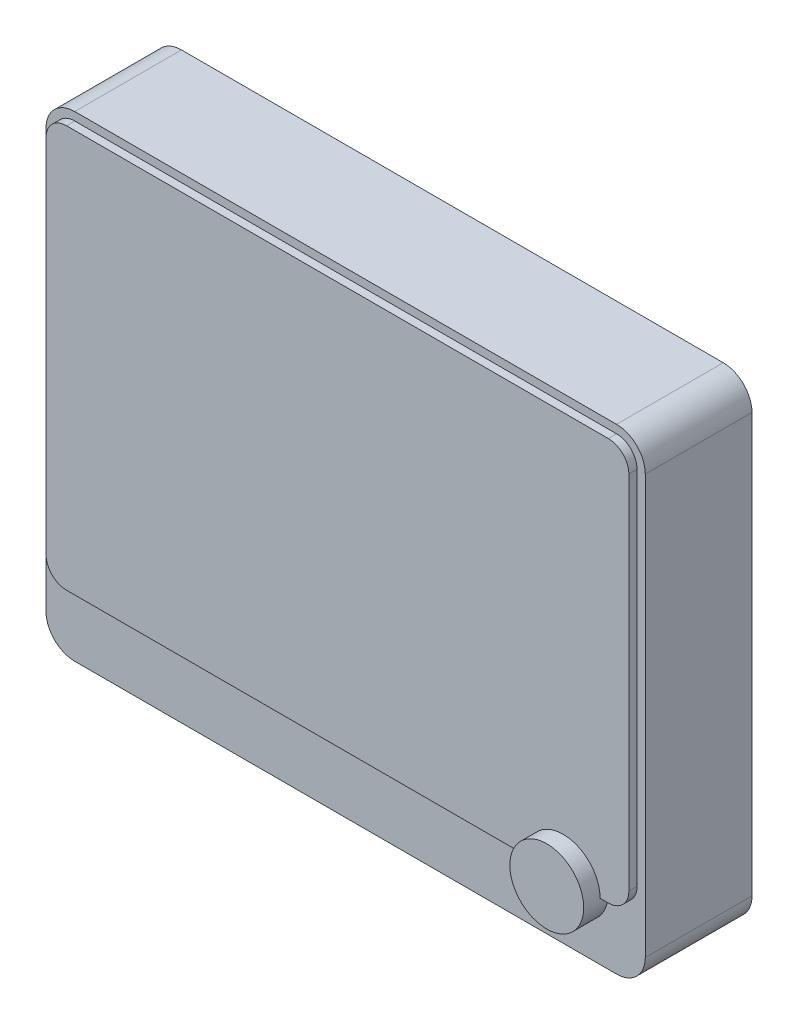
SolidWorks part; units mm, degrees
ref_plane "Front Plane" through (0, 0, 0) normal (0, 0, 1) x (1, 0, 0)
ref_plane "Top Plane" through (0, 0, 0) normal (0, 1, 0) x (1, 0, 0)
ref_plane "Right Plane" through (0, 0, 0) normal (1, 0, 0) x (0, 0, -1)
sketch "Sketch1" plane through (0, 0, 0) normal (0, 0, 1) x (1, 0, 0)
  line L0 (0, 0) -> (73, 0)
  line L1 (73, 0) -> (73, 58)
  line L2 (73, 58) -> (0, 58)
  line L3 (0, 58) -> (0, 0)
extrude "Boss-Extrude1" add sketch "Sketch1" along normal blind 13
fillet "Fillet1" radius 3.5 4 edges at (73, 0, 6.5) (0, 0, 6.5) (0, 58, 6.5) (73, 58, 6.5)
sketch "Sketch2" plane through (0, 0, 13) normal (0, 0, 1) x (1, 0, 0)
  line L5 (3.5, 8) -> (69.5, 8)
  line L8 (3.5, 1) -> (69.5, 1)
  line L9 (72, 3.5) -> (72, 54.5)
  line L10 (69.5, 57) -> (3.5, 57)
  line L11 (1, 54.5) -> (1, 3.5)
  line L13 (72, 10.5) -> (72, 54.5)
  line L14 (69.5, 57) -> (3.5, 57)
  line L15 (1, 54.5) -> (1, 10.5)
  arc A4 (1, 10.5) -> (3.5, 8) centre (3.5, 10.5) ccw
  arc A5 (72, 10.5) -> (69.5, 8) centre (69.5, 10.5) cw
  arc A8 (69.5, 1) -> (72, 3.5) centre (69.5, 3.5) ccw
  arc A9 (72, 54.5) -> (69.5, 57) centre (69.5, 54.5) ccw
  arc A10 (3.5, 57) -> (1, 54.5) centre (3.5, 54.5) ccw
  arc A11 (1, 3.5) -> (3.5, 1) centre (3.5, 3.5) ccw
  arc A13 (72, 54.5) -> (69.5, 57) centre (69.5, 54.5) ccw
  arc A14 (3.5, 57) -> (1, 54.5) centre (3.5, 54.5) ccw
  dimension "D1" = 1
extrude "Boss-Extrude2" add sketch "Sketch2" along normal blind 1
sketch "Sketch3" plane through (0, 0, 13) normal (0, 0, 1) x (1, 0, 0)
  line L2 (3.5, 8) -> (69.5, 8) construction
  circle A0 centre (64, 8) radius 4.5
extrude "Boss-Extrude3" add sketch "Sketch3" along normal blind 3
sketch "Sketch6" plane through (0, 0, 0) normal (0, 0, -1) x (-1, 0, 0)
  line L1 (-63, 48) -> (-10, 48)
  line L2 (-63, 48) -> (-63, 42)
  line L3 (-63, 42) -> (-10, 42)
  line L4 (-10, 48) -> (-10, 42)
extrude "Cut-Extrude2" cut sketch "Sketch6" against normal blind 1
